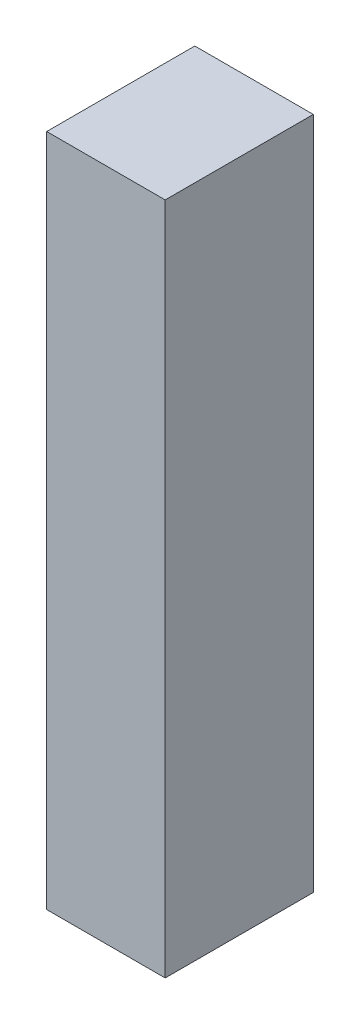
SolidWorks part; units mm, degrees
ref_plane "Front Plane" through (0, 0, 0) normal (0, 0, 1) x (1, 0, 0)
ref_plane "Top Plane" through (0, 0, 0) normal (0, 1, 0) x (1, 0, 0)
ref_plane "Right Plane" through (0, 0, 0) normal (1, 0, 0) x (0, 0, -1)
sketch "Sketch1" plane through (0, 0, 0) normal (0, 0, 1) x (1, 0, 0)
  line L1 (-8, -45.5) -> (8, -45.5)
  line L2 (-8, -45.5) -> (-8, 45.5)
  line L3 (-8, 45.5) -> (8, 45.5)
  line L4 (8, -45.5) -> (8, 45.5)
  line L5 (-8, -45.5) -> (8, 45.5) construction
  line L6 (-8, 45.5) -> (8, -45.5) construction
  point P0 (0, 0)
  dimension "D1" = 91
  dimension "D2" = 16
extrude "Boss-Extrude1" add sketch "Sketch1" along normal blind 20
